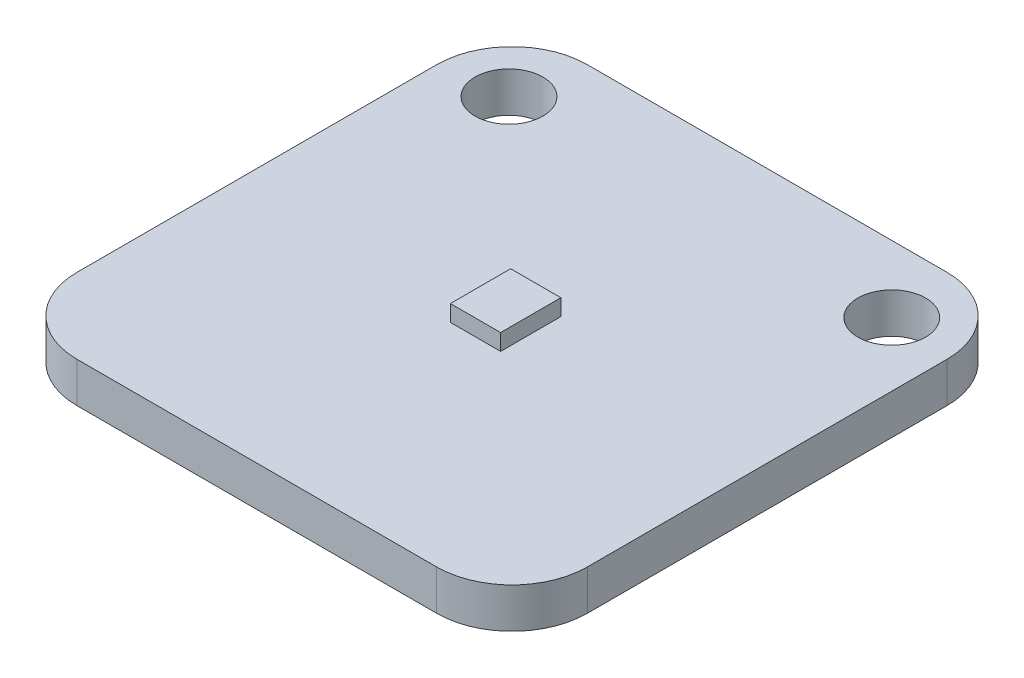
SolidWorks part; units mm, degrees
ref_plane "Front Plane" through (0, 0, 0) normal (0, 0, 1) x (1, 0, 0)
ref_plane "Top Plane" through (0, 0, 0) normal (0, 1, 0) x (1, 0, 0)
ref_plane "Right Plane" through (0, 0, 0) normal (1, 0, 0) x (0, 0, -1)
sketch "Sketch2" plane through (0, 0, 0) normal (0, 1, 0) x (1, 0, 0)
  line L1 (-7.16, 10.16) -> (7.16, 10.16)
  line L2 (-10.16, 7.16) -> (-10.16, -7.16)
  line L3 (-7.16, -10.16) -> (7.16, -10.16)
  line L4 (10.16, 7.16) -> (10.16, -7.16)
  line L5 (-10.16, 10.16) -> (10.16, -10.16) construction
  line L6 (-10.16, -10.16) -> (10.16, 10.16) construction
  arc A0 (-10.16, -7.16) -> (-7.16, -10.16) centre (-7.16, -7.16) ccw
  arc A1 (7.16, -10.16) -> (10.16, -7.16) centre (7.16, -7.16) ccw
  arc A2 (10.16, 7.16) -> (7.16, 10.16) centre (7.16, 7.16) ccw
  arc A3 (-7.16, 10.16) -> (-10.16, 7.16) centre (-7.16, 7.16) ccw
  point P0 (0, 0)
  dimension "D3" = 3
  dimension "D1" = 20.32
  dimension "D2" = 20.32
extrude "FR4" add sketch "Sketch2" along normal blind 1.6
sketch "Sketch4" plane through (0, 0, 0) normal (0, 1, 0) x (1, 0, 0)
  line L0 (0, 0) -> (0, 10.16) construction
  line L1 (7.16, 10.16) -> (-7.16, 10.16) construction
  line L2 (-7.62, 8.85) -> (-12.0916, 8.85) construction
  circle A0 centre (-7.62, 7.5) radius 1.35
  circle A1 centre (7.62, 7.5) radius 1.35
  dimension "D3" = 2.7
  dimension "D1" = 15.24
  dimension "D2" = 1.31
extrude "holes-mounting" cut sketch "Sketch4" along normal through all
sketch "Sketch5" plane through (0, 1.6, 0) normal (0, 1, 0) x (1, 0, 0)
  line L0 (7.16, 10.16) -> (-7.16, 10.16) construction
  line L1 (-1, 0.946) -> (1, 0.946)
  line L2 (-1, 0.946) -> (-1, -1.454)
  line L3 (-1, -1.454) -> (1, -1.454)
  line L4 (1, 0.946) -> (1, -1.454)
  line L5 (-1, 0.946) -> (1, -1.454) construction
  line L6 (-1, -1.454) -> (1, 0.946) construction
  line L7 (0, 10.16) -> (0, -10.16) construction
  line L8 (-7.16, -10.16) -> (7.16, -10.16) construction
  line L9 (10.16, -7.16) -> (10.16, 7.16) construction
  line L10 (-10.16, 7.16) -> (-10.16, -7.16) construction
  point P0 (0, -0.254)
  dimension "D1" = 2
  dimension "D2" = 2.4
  dimension "D3" = 10.414
extrude "TCS34725" add sketch "Sketch5" along normal blind 0.65 separate body
